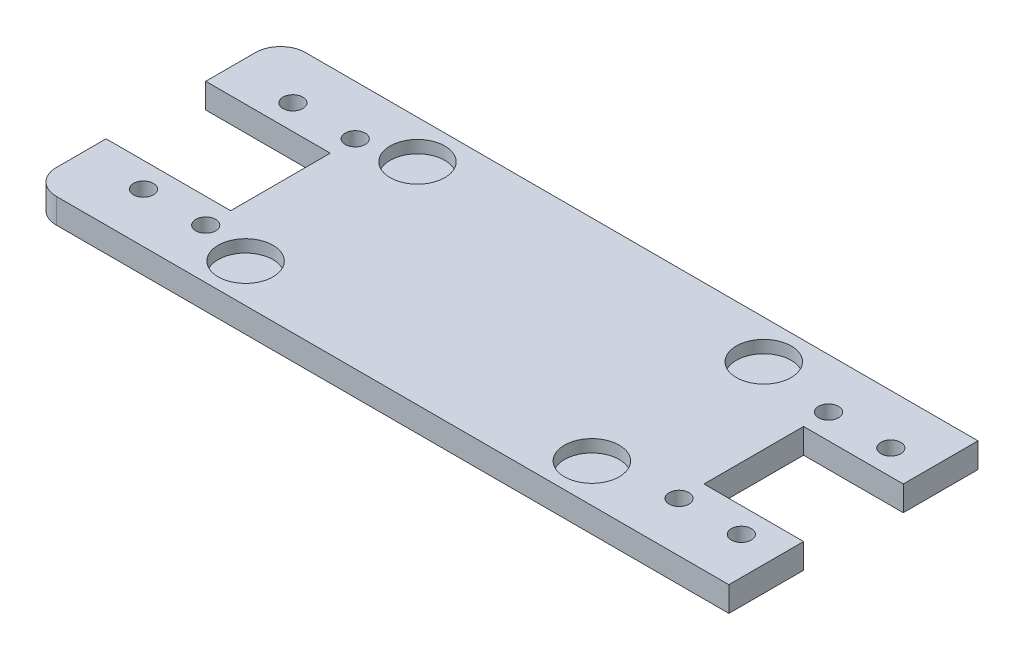
SolidWorks part; units mm, degrees
ref_plane "前视基准面" through (0, 0, 0) normal (0, 0, 1) x (1, 0, 0)
ref_plane "上视基准面" through (0, 0, 0) normal (0, 1, 0) x (1, 0, 0)
ref_plane "右视基准面" through (0, 0, 0) normal (1, 0, 0) x (0, 0, -1)
other "Configuration Table"
sketch "草图3" plane through (0, 0, 0) normal (0, 1, 0) x (1, 0, 0)
  line L1 (-140, 50) -> (140, 50)
  line L2 (-140, 50) -> (-140, -50)
  line L3 (-140, -50) -> (140, -50)
  line L4 (140, 50) -> (140, -50)
  line L5 (-140, 50) -> (140, -50) construction
  line L6 (-140, -50) -> (140, 50) construction
  point P0 (0, 0)
  dimension "D1" = 280
  dimension "D2" = 100
extrude "凸台-拉伸1" add sketch "草图3" along normal blind 10
sketch "草图5" plane through (0, 10, 0) normal (0, 1, 0) x (1, 0, 0)
  line L0 (-140, 50) -> (-140, -50) construction
  circle A0 centre (-115, -30) radius 4
  circle A1 centre (-90, -30) radius 4
  dimension "D1" = 25
  dimension "D2" = 25
extrude "切除-拉伸1" cut sketch "草图5" against normal through all
mirror "镜向1" about plane through (0, 0, 0) normal (0, 0, 1) of "切除-拉伸1"
sketch "草图6" plane through (0, 10, 0) normal (0, 1, 0) x (1, 0, 0)
  line L0 (140, -50) -> (140, 50) construction
  circle A0 centre (125, 30) radius 4
  circle A1 centre (100, 30) radius 4
  dimension "D1" = 25
  dimension "D2" = 15
extrude "切除-拉伸2" cut sketch "草图6" against normal blind 10
mirror "镜向2" about plane through (0, 0, 0) normal (0, 0, 1) of "切除-拉伸2"
sketch "草图7" plane through (0, 10, 0) normal (0, 1, 0) x (1, 0, 0)
  line L0 (-140, 20) -> (-90, 20)
  line L1 (-140, 50) -> (-140, -50) construction
  line L2 (-90, 20) -> (-90, -20)
  line L3 (-90, -20) -> (-140, -20)
  line L4 (-140, -20) -> (-140, 20)
  dimension "D1" = 30
  dimension "D2" = 30
  dimension "D3" = 50
extrude "切除-拉伸3" cut sketch "草图7" against normal through all
fillet "圆角1" radius 10 1 edges at (-140, 5, 50)
fillet "圆角2" radius 10 1 edges at (-140, 5, -50)
sketch "草图8" plane through (0, 10, 0) normal (0, 1, 0) x (1, 0, 0)
  line L0 (140, 20) -> (100, 20)
  line L1 (140, -50) -> (140, 50) construction
  line L2 (100, 20) -> (100, -20)
  line L3 (100, -20) -> (140, -20)
  line L4 (140, -20) -> (140, 20)
  dimension "D1" = 40
  dimension "D2" = 40
extrude "切除-拉伸4" cut sketch "草图8" against normal through all
sketch "草图11" plane through (0, 10, 0) normal (0, 1, 0) x (1, 0, 0)
  line L0 (0, 0) -> (0, 24.3973)
  line L1 (-82.5, 47.5) -> (82.5, 47.5)
  line L2 (-82.5, 47.5) -> (-82.5, -47.5)
  line L3 (-82.5, -47.5) -> (82.5, -47.5)
  line L4 (82.5, 47.5) -> (82.5, -47.5)
  line L5 (-82.5, 47.5) -> (82.5, -47.5) construction
  line L6 (-82.5, -47.5) -> (82.5, 47.5) construction
  line L7 (0, 0) -> (-18.448, 0)
  circle A1 centre (-69.5, 34.5) radius 11
  circle A2 centre (69.5, 34.5) radius 11
  circle A3 centre (69.5, -34.5) radius 11
  circle A4 centre (-69.5, -34.5) radius 11
  point P0 (0, 0)
  dimension "D5" = 22
  dimension "D1" = 95
  dimension "D2" = 165
  dimension "D3" = 13
  dimension "D4" = 13
extrude "切除-拉伸5" cut sketch "草图11" against normal blind 5 contours A4 | A1 | A2 | A3
